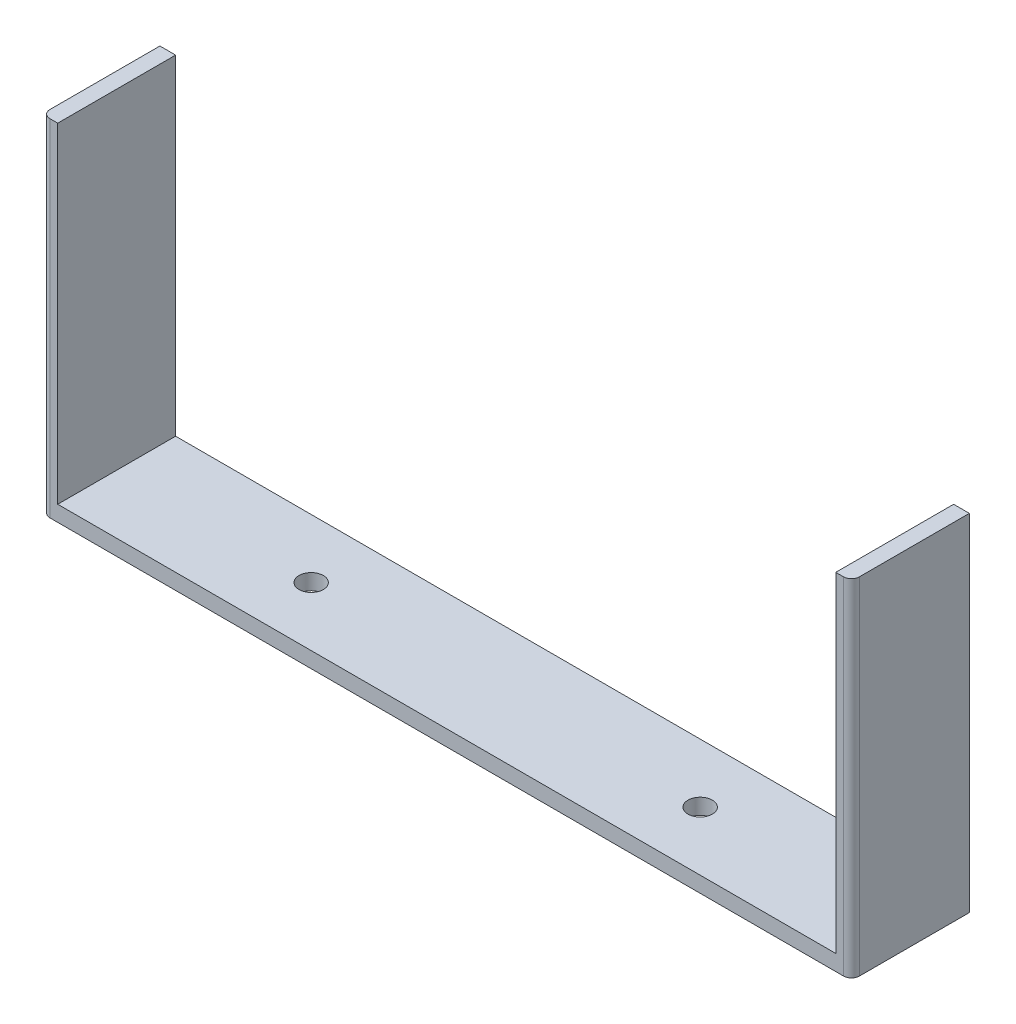
SolidWorks part; units mm, degrees
ref_plane "Plano frontal" through (0, 0, 0) normal (0, 0, 1) x (1, 0, 0)
ref_plane "Plano superior" through (0, 0, 0) normal (0, 1, 0) x (1, 0, 0)
ref_plane "Plano direito" through (0, 0, 0) normal (1, 0, 0) x (0, 0, -1)
sketch "Esboço1" plane through (0, 0, 0) normal (0, 1, 0) x (1, 0, 0)
  line L1 (51.5, -7.5) -> (-51.5, -7.5)
  line L2 (51.5, -7.5) -> (51.5, 7.5)
  line L3 (51.5, 7.5) -> (-51.5, 7.5)
  line L4 (-51.5, -7.5) -> (-51.5, 7.5)
  line L5 (51.5, -7.5) -> (-51.5, 7.5) construction
  line L6 (51.5, 7.5) -> (-51.5, -7.5) construction
  point P0 (0, 0)
  dimension "D1" = 103
  dimension "D2" = 15
extrude "Ressalto-extrusão1" add sketch "Esboço1" against normal blind 2
sketch "Esboço2" plane through (0, 0, 0) normal (0, 1, 0) x (1, 0, 0)
  line L22 (-51.5, 7.5) -> (-51.5, -7.5) construction
  line L23 (-51.5, 7.5) -> (-51.5, -7.5)
  line L24 (-49.5, 7.5) -> (-49.5, -7.5)
  line L25 (-49.5, 7.5) -> (-51.5, 7.5)
  line L26 (-49.5, -7.5) -> (-51.5, -7.5)
  line L27 (0, 0) -> (0, -7.5) construction
  line L28 (-51.5, -7.5) -> (51.5, -7.5) construction
  line L29 (49.5, -7.5) -> (51.5, -7.5)
  line L30 (49.5, 7.5) -> (51.5, 7.5)
  line L31 (49.5, 7.5) -> (49.5, -7.5)
  line L32 (51.5, 7.5) -> (51.5, -7.5)
  dimension "D1" = 2
extrude "Ressalto-extrusão2" add sketch "Esboço2" along normal blind 42
sketch "Esboço4" plane through (0, 0, 0) normal (0, 1, 0) x (1, 0, 0)
  line L0 (0, 0) -> (49.5, 0) construction
  line L1 (49.5, 7.5) -> (49.5, -7.5) construction
  line L2 (0, 0) -> (0, 7.5) construction
  line L3 (49.5, 7.5) -> (-49.5, 7.5) construction
  circle A0 centre (24.75, 0) radius 1.55
  circle A1 centre (-24.75, 0) radius 1.55
  dimension "D1" = 3.1
extrude "Corte-extrusão1" cut sketch "Esboço4" against normal blind 2
fillet "Filete1" radius 1 2 edges at (51.5, 20, 7.5) (-51.5, 20, 7.5)
